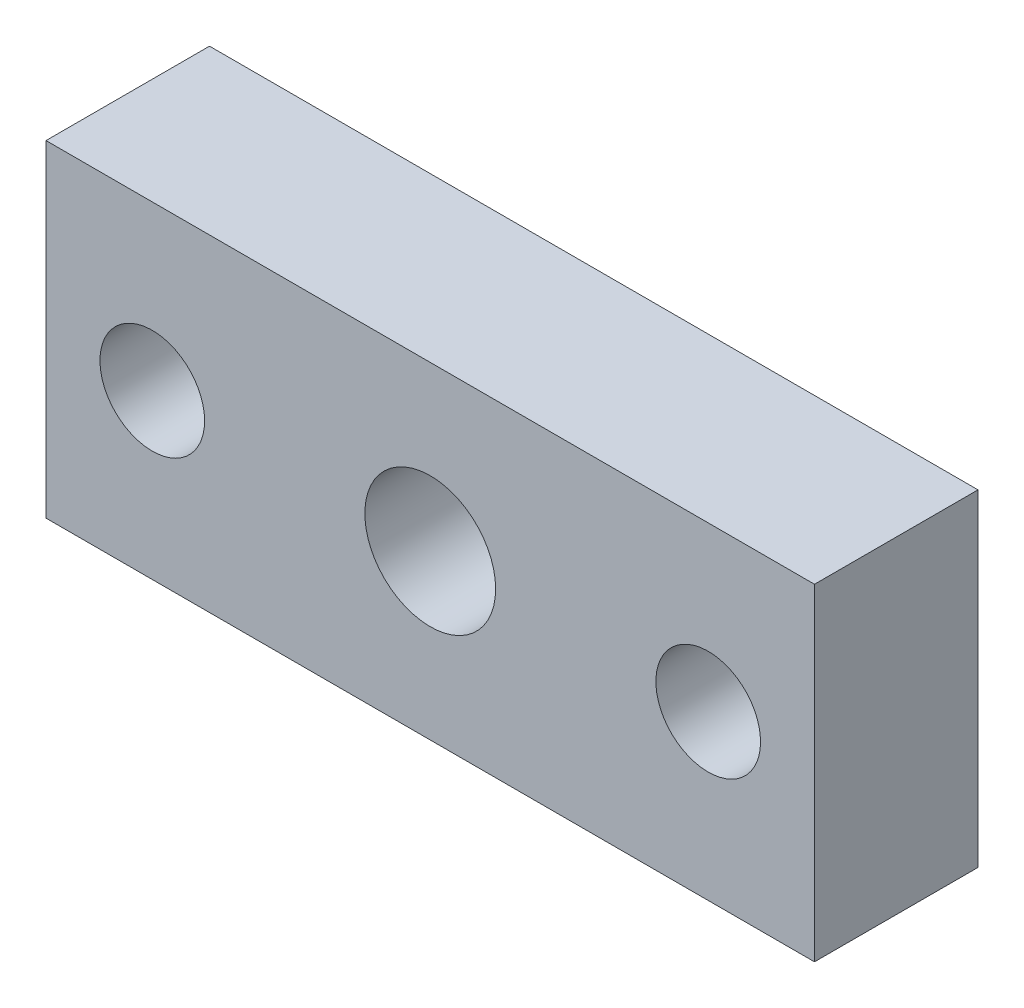
SolidWorks part; units mm, degrees
material "普通碳钢"
ref_plane "前视基准面" through (0, 0, 0) normal (0, 0, 1) x (1, 0, 0)
ref_plane "上视基准面" through (0, 0, 0) normal (0, 1, 0) x (1, 0, 0)
ref_plane "右视基准面" through (0, 0, 0) normal (1, 0, 0) x (0, 0, -1)
sketch "草图1" plane through (0, 0, 0) normal (0, 0, 1) x (1, 0, 0)
  line L0 (-1000, 0) -> (49000, 0) construction
  line L1 (-11.75, -5) -> (11.75, -5)
  line L2 (-11.75, -5) -> (-11.75, 5)
  line L3 (-11.75, 5) -> (11.75, 5)
  line L4 (11.75, -5) -> (11.75, 5)
  line L5 (-11.75, -5) -> (11.75, 5) construction
  line L6 (-11.75, 5) -> (11.75, -5) construction
  circle A0 centre (-8.5, 0) radius 1.6
  circle A1 centre (8.5, 0) radius 1.6
  point P0 (0, 0)
  dimension "D3" = 3.2
  dimension "D4" = 8.5
  dimension "D5" = 8.5
  dimension "D1" = 10
  dimension "D2" = 23.5
extrude "凸台-拉伸1" add sketch "草图1" along normal blind 5
sketch "草图2" plane through (0, 0, 5) normal (0, 0, 1) x (1, 0, 0)
  circle A0 centre (0, 0) radius 2
  dimension "D1" = 4
extrude "切除-拉伸1" cut sketch "草图2" against normal blind 10
